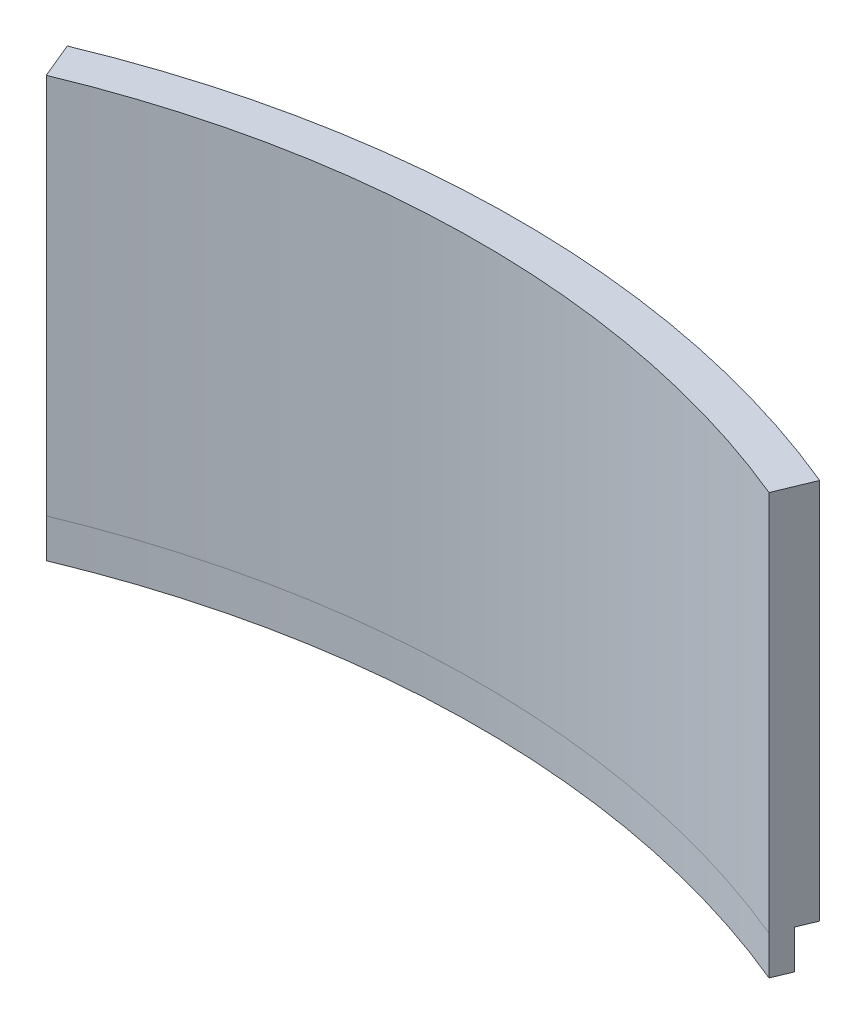
SolidWorks part; units mm, degrees
ref_plane "Front Plane" through (0, 0, 0) normal (0, 0, 1) x (1, 0, 0)
ref_plane "Top Plane" through (0, 0, 0) normal (0, 1, 0) x (1, 0, 0)
ref_plane "Right Plane" through (0, 0, 0) normal (1, 0, 0) x (0, 0, -1)
sketch "Sketch1" plane through (0, 0, 0) normal (0, 1, 0) x (1, 0, 0)
  line L0 (0, 83.7441) -> (0, -50.6) construction
  line L1 (-73.8008, 0) -> (59.4384, 0) construction
  line L2 (0, 0) -> (29.0839, 70.2148) construction
  line L3 (0, 0) -> (-29.0839, 70.2148) construction
  line L4 (29.0839, 70.2148) -> (27.9359, 67.4432)
  line L5 (-29.0839, 70.2148) -> (-27.9359, 67.4432)
  arc A0 (-29.0839, 70.2148) -> (29.0839, 70.2148) centre (0, 0) cw
  arc A1 (-27.9359, 67.4432) -> (27.9359, 67.4432) centre (0, 0) cw
  dimension "D1" = 76
  dimension "D2" = 45
  dimension "D3" = 3
extrude "Boss-Extrude1" add sketch "Sketch1" along normal blind 26.5
sketch "Sketch2" plane through (0, 0, 0) normal (0, -1, 0) x (1, 0, 0)
  line L0 (-29.0839, -70.2148) -> (-27.9359, -67.4432) construction
  line L1 (27.9359, -67.4432) -> (29.0839, -70.2148) construction
  line L2 (27.9359, -67.4432) -> (29.0839, -70.2148)
  line L3 (-29.0839, -70.2148) -> (-27.9359, -67.4432)
  arc A0 (-29.0839, -70.2148) -> (29.0839, -70.2148) centre (0, 0) ccw
  arc A1 (-27.9359, -67.4432) -> (27.9359, -67.4432) centre (0, 0) ccw construction
  arc A2 (-27.9359, -67.4432) -> (27.9359, -67.4432) centre (0, 0) ccw
  point P10 (29.0839, -70.2148)
  dimension "D2" = 76
extrude "Boss-Extrude2" add sketch "Sketch2" along normal blind 3
sketch "Sketch3" plane through (0, -3, 0) normal (0, -1, 0) x (1, 0, 0)
  line L0 (27.9359, -67.4432) -> (28.5099, -68.829)
  line L1 (29.0839, -70.2148) -> (27.9359, -67.4432) construction
  line L2 (-27.9359, -67.4432) -> (-29.0839, -70.2148) construction
  line L3 (-27.9359, -67.4432) -> (-28.5099, -68.829)
  arc A0 (-27.9359, -67.4432) -> (27.9359, -67.4432) centre (0, -0.2524) ccw
  arc A1 (28.5099, -68.829) -> (-28.5099, -68.829) centre (0, -0.2524) cw
extrude "Boss-Extrude3" add sketch "Sketch3" along normal blind 3
